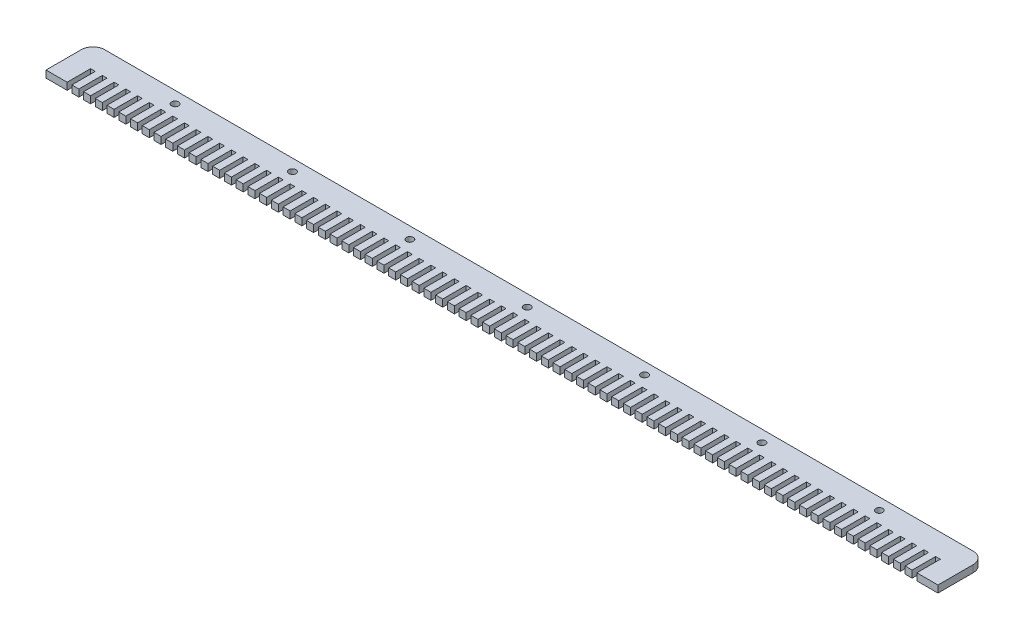
SolidWorks part; units mm, degrees
ref_plane "Front Plane" through (0, 0, 0) normal (0, 0, 1) x (1, 0, 0)
ref_plane "Top Plane" through (0, 0, 0) normal (0, 1, 0) x (1, 0, 0)
ref_plane "Right Plane" through (0, 0, 0) normal (1, 0, 0) x (0, 0, -1)
sketch "Sketch1" plane through (0, 0, 0) normal (0, 1, 0) x (1, 0, 0)
  line L1 (-190, -10) -> (190, -10)
  line L2 (-190, -10) -> (-190, 10)
  line L3 (-190, 10) -> (190, 10)
  line L4 (190, -10) -> (190, 10)
  line L5 (-190, -10) -> (190, 10) construction
  line L6 (-190, 10) -> (190, -10) construction
  point P0 (0, 0)
  dimension "D1" = 380
  dimension "D2" = 20
extrude "Extrude1" add sketch "Sketch1" along normal blind 3
sketch "Sketch2" plane through (0, 3, 0) normal (0, 1, 0) x (1, 0, 0)
  line L0 (-190, -10) -> (190, -10) construction
  line L1 (-1, 0) -> (1, 0)
  line L2 (-1, 0) -> (-1, -10)
  line L3 (-1, -10) -> (1, -10)
  line L4 (1, 0) -> (1, -10)
  line L5 (-1, 0) -> (1, -10) construction
  line L6 (-1, -10) -> (1, 0) construction
  line L7 (0, -5) -> (0, 0) construction
  point P0 (0, -5)
  dimension "D1" = 2
  dimension "D2" = 10
extrude "Extrude2" cut sketch "Sketch2" against normal up to next
pattern_linear "LPattern2" count 37 spacing 5 along (1, 0, 0) count 37 spacing 5 along (-1, 0, 0) of "Extrude2"
sketch "Sketch3" plane through (0, 3, 0) normal (0, 1, 0) x (1, 0, 0)
  line L0 (0, 0) -> (0, 5) construction
  circle A0 centre (0, 5) radius 1.5
  dimension "D1" = 3
  dimension "D2" = 5
extrude "Cut-Extrude1" cut sketch "Sketch3" against normal up to next
pattern_linear "LPattern3" count 4 spacing 50 along (-1, 0, 0) count 4 spacing 50 along (1, 0, 0) of "Cut-Extrude1"
fillet "Fillet1" radius 5 2 edges at (-190, 1.5, -10) (190, 1.5, -10)
